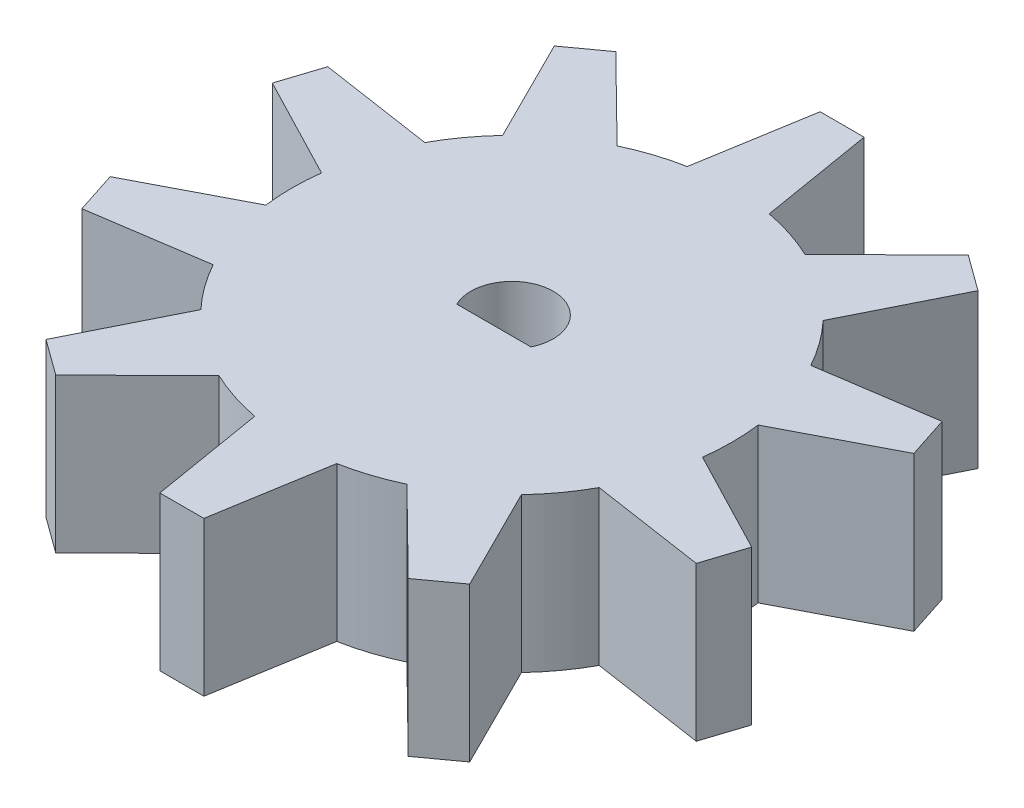
SolidWorks part; units mm, degrees
ref_plane "Front Plane" through (0, 0, 0) normal (0, 0, 1) x (1, 0, 0)
ref_plane "Top Plane" through (0, 0, 0) normal (0, 1, 0) x (1, 0, 0)
ref_plane "Right Plane" through (0, 0, 0) normal (1, 0, 0) x (0, 0, -1)
sketch "Sketch1" plane through (0, 0, 0) normal (0, 1, 0) x (1, 0, 0)
  line L0 (0, 15) -> (0, 10) construction
  line L1 (-1, 15) -> (1, 15)
  line L2 (-1, 15) -> (-2, 9)
  line L3 (1, 15) -> (2, 9)
  line L4 (-2, 9) -> (2, 9)
  line L5 (3.672, 8.4567) -> (6.9081, 6.1056)
  line L6 (9.6258, 11.5475) -> (6.9081, 6.1056)
  line L7 (8.0078, 12.723) -> (9.6258, 11.5475)
  line L8 (8.0078, 12.723) -> (3.672, 8.4567)
  line L9 (7.9415, 4.6833) -> (9.1775, 0.879)
  line L10 (14.5749, 3.6842) -> (9.1775, 0.879)
  line L11 (13.9568, 5.5863) -> (14.5749, 3.6842)
  line L12 (13.9568, 5.5863) -> (7.9415, 4.6833)
  line L13 (9.1775, -0.879) -> (7.9415, -4.6833)
  line L14 (13.9568, -5.5863) -> (7.9415, -4.6833)
  line L15 (14.5749, -3.6842) -> (13.9568, -5.5863)
  line L16 (14.5749, -3.6842) -> (9.1775, -0.879)
  line L17 (6.9081, -6.1056) -> (3.672, -8.4567)
  line L18 (8.0078, -12.723) -> (3.672, -8.4567)
  line L19 (9.6258, -11.5475) -> (8.0078, -12.723)
  line L20 (9.6258, -11.5475) -> (6.9081, -6.1056)
  line L21 (2, -9) -> (-2, -9)
  line L22 (-1, -15) -> (-2, -9)
  line L23 (1, -15) -> (-1, -15)
  line L24 (1, -15) -> (2, -9)
  line L25 (-3.672, -8.4567) -> (-6.9081, -6.1056)
  line L26 (-9.6258, -11.5475) -> (-6.9081, -6.1056)
  line L27 (-8.0078, -12.723) -> (-9.6258, -11.5475)
  line L28 (-8.0078, -12.723) -> (-3.672, -8.4567)
  line L29 (-7.9415, -4.6833) -> (-9.1775, -0.879)
  line L30 (-14.5749, -3.6842) -> (-9.1775, -0.879)
  line L31 (-13.9568, -5.5863) -> (-14.5749, -3.6842)
  line L32 (-13.9568, -5.5863) -> (-7.9415, -4.6833)
  line L33 (-9.1775, 0.879) -> (-7.9415, 4.6833)
  line L34 (-13.9568, 5.5863) -> (-7.9415, 4.6833)
  line L35 (-14.5749, 3.6842) -> (-13.9568, 5.5863)
  line L36 (-14.5749, 3.6842) -> (-9.1775, 0.879)
  line L37 (-6.9081, 6.1056) -> (-3.672, 8.4567)
  line L38 (-8.0078, 12.723) -> (-3.672, 8.4567)
  line L39 (-9.6258, 11.5475) -> (-8.0078, 12.723)
  line L40 (-9.6258, 11.5475) -> (-6.9081, 6.1056)
  line L41 (0, 9) -> (0, 10) construction
  circle A0 centre (0, 0) radius 10
  circle A1 centre (0, 0) radius 15 construction
  point P9 (0, 15)
  point P50 (0, 0)
  dimension "D1" = 5
  dimension "D2" = 20
  dimension "D3" = 2
  dimension "D4" = 4
  dimension "D6" = 1
  dimension "D7" = 1
  dimension "D5" = 10
extrude "Boss-Extrude2" add sketch "Sketch1" along normal blind 7 contours L24 A0 L18 L17 L20 L14 L13 L16 L10 L9 L12 L6 L5 L8 L3 L4 L2 L38 L37 L40 L34 L33 L36 L30 L29 L32 L26 L25 L28 L22 L21 | A0 L30 L31 L32 | A0 L26 L27 L28 | A0 L22 L23 L24 | A0 L18 L19 L20 | A0 L14 L15 L16 | A0 L10 L11 L12 | A0 L6 L7 L8 | A0 L3 L1 L2 | A0 L38 L39 L40 | A0 L34 L35 L36 | L34 A0 L36 L33 | L22 A0 L24 L21 | L18 A0 L20 L17 | L26 A0 L28 L25 | L30 A0 L32 L29 | L38 A0 L40 L37 | L3 A0 L2 L4 | L6 A0 L8 L5 | L10 A0 L12 L9 | L14 A0 L16 L13
sketch "Sketch3" plane through (0, 0, 0) normal (0, -1, 0) x (1, 0, 0)
  line L0 (-1.6837, 0.825) -> (1.6837, 0.825)
  line L1 (0, 0.825) -> (0, -1.875) construction
  arc A0 (-1.6837, 0.825) -> (1.6837, 0.825) centre (0, 0) ccw
  dimension "D1" = 3.75
  dimension "D2" = 2.7
extrude "Cut-Extrude1" cut sketch "Sketch3" against normal blind 7
